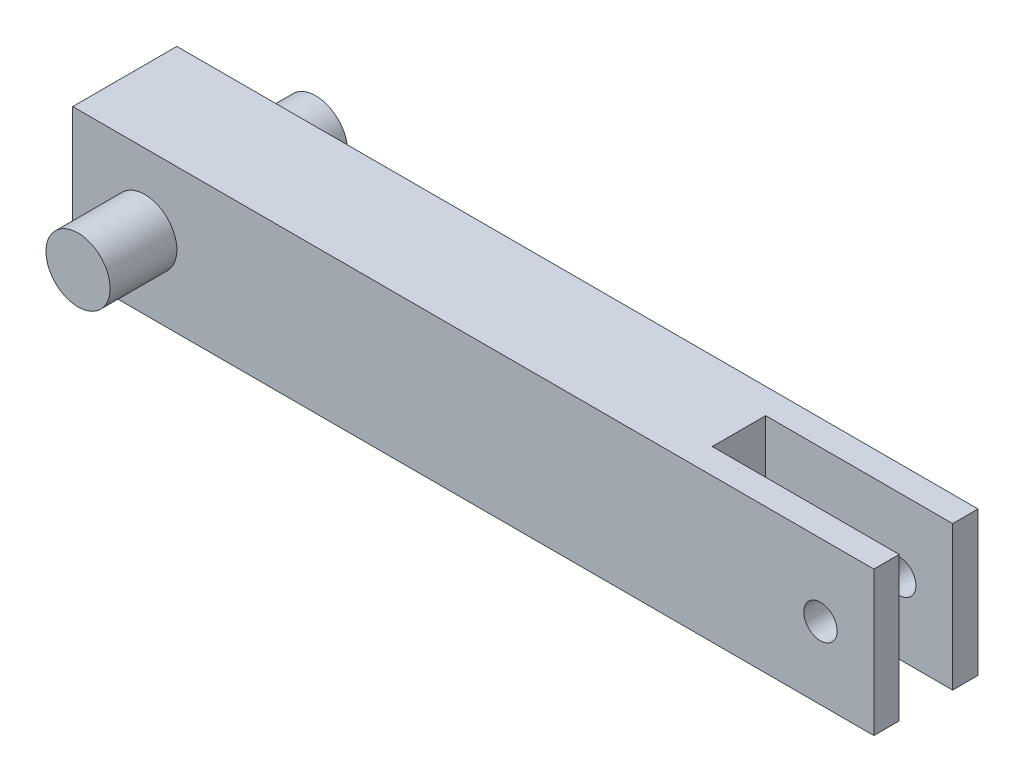
SolidWorks part; units mm, degrees
ref_plane "Front Plane" through (0, 0, 0) normal (0, 0, 1) x (1, 0, 0)
ref_plane "Top Plane" through (0, 0, 0) normal (0, 1, 0) x (1, 0, 0)
ref_plane "Right Plane" through (0, 0, 0) normal (1, 0, 0) x (0, 0, -1)
sketch "Sketch1" plane through (0, 0, 0) normal (0, 1, 0) x (1, 0, 0)
  line L1 (-300, 39) -> (300, 39)
  line L2 (-300, 39) -> (-300, -39)
  line L3 (-300, -39) -> (300, -39)
  line L4 (300, 39) -> (300, -39)
  line L5 (-300, 39) -> (300, -39) construction
  line L6 (-300, -39) -> (300, 39) construction
  point P0 (0, 0)
  dimension "D1" = 600
  dimension "D2" = 78
extrude "Boss-Extrude1" add sketch "Sketch1" along normal blind 108
sketch "Sketch2" plane through (0, 0, 39) normal (0, 0, 1) x (1, 0, 0)
  line L0 (-300, 108) -> (-300, 0) construction
  line L1 (-300, 108) -> (300, 108) construction
  circle A0 centre (-246, 54) radius 24
  dimension "D1" = 54
  dimension "D2" = 48
  dimension "D3" = 54
extrude "Boss-Extrude2" add sketch "Sketch2" along normal blind 50
sketch "Sketch3" plane through (0, 0, -39) normal (0, 0, -1) x (-1, 0, 0)
  line L0 (-300, 108) -> (300, 108) construction
  line L1 (300, 108) -> (300, 0) construction
  circle A0 centre (246, 54) radius 24
  dimension "D1" = 48
  dimension "D2" = 54
  dimension "D3" = 54
extrude "Boss-Extrude3" add sketch "Sketch3" along normal blind 50
sketch "Sketch4" plane through (0, 0, 0) normal (0, -1, 0) x (-1, 0, 0)
  line L0 (-300, -39) -> (-300, 39) construction
  line L1 (-160, 20) -> (-300, 20)
  line L2 (-160, 20) -> (-160, -20)
  line L3 (-160, -20) -> (-300, -20)
  line L4 (-300, 20) -> (-300, -20)
  line L5 (-160, 20) -> (-300, -20) construction
  line L6 (-160, -20) -> (-300, 20) construction
  point P0 (-230, 0)
  dimension "D1" = 140
  dimension "D2" = 40
extrude "Cut-Extrude1" cut sketch "Sketch4" against normal through all
sketch "Sketch5" plane through (0, 0, -39) normal (0, 0, -1) x (-1, 0, 0)
  line L0 (-300, 108) -> (300, 108) construction
  line L1 (-300, 108) -> (-300, 0) construction
  circle A0 centre (-260, 54) radius 12.5
  dimension "D1" = 25
  dimension "D2" = 54
  dimension "D3" = 40
extrude "Cut-Extrude2" cut sketch "Sketch5" against normal through all
